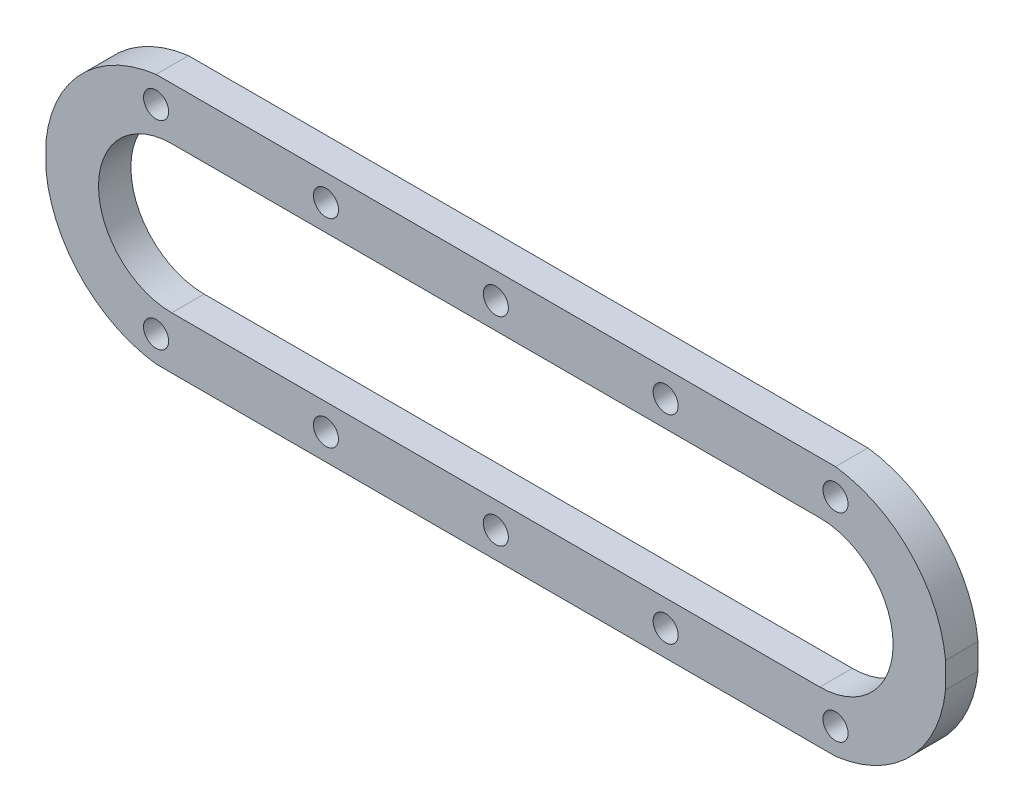
SolidWorks part; units mm, degrees
ref_plane "Front" through (0, 0, 0) normal (0, 0, 1) x (1, 0, 0)
ref_plane "Top" through (0, 0, 0) normal (0, 1, 0) x (1, 0, 0)
ref_plane "Right" through (0, 0, 0) normal (1, 0, 0) x (0, 0, -1)
sketch "Sketch1" plane through (0, 0, 0) normal (0, 0, 1) x (1, 0, 0)
  line L1 (88.138, 24.5745) -> (-88.138, 24.5745)
  line L2 (88.138, 24.5745) -> (88.138, -24.5745)
  line L3 (88.138, -24.5745) -> (-88.138, -24.5745)
  line L4 (-88.138, 24.5745) -> (-88.138, -24.5745)
  line L5 (88.138, 24.5745) -> (-88.138, -24.5745) construction
  line L6 (88.138, -24.5745) -> (-88.138, 24.5745) construction
  point P0 (0, 0)
  dimension "D1" = 176.276
  dimension "D2" = 49.149
extrude "Boss-Extrude1" add sketch "Sketch1" along normal blind 6.35
sketch "Sketch2" plane through (0, 0, 6.35) normal (0, 0, 1) x (1, 0, 0)
  line L0 (63.5, 0) -> (-63.5, 0) construction
  line L1 (63.5, -14.351) -> (-63.5, -14.351)
  line L2 (63.5, 14.351) -> (-63.5, 14.351)
  arc A0 (63.5, -14.351) -> (63.5, 14.351) centre (63.5, 0) ccw
  arc A1 (-63.5, 14.351) -> (-63.5, -14.351) centre (-63.5, 0) ccw
  point P2 (0, 0)
  dimension "D1" = 127
  dimension "D2" = 28.702
extrude "Cut-Extrude1" cut sketch "Sketch2" against normal through all
sketch "Sketch8" plane through (0, 0, 6.35) normal (0, 0, 1) x (1, 0, 0)
  line L4 (-63.5, 24.765) -> (63.5, 24.765)
  line L5 (-63.5, 14.351) -> (63.5, 14.351)
  line L6 (-63.5, -14.351) -> (63.5, -14.351)
  line L7 (-63.5, -24.765) -> (63.5, -24.765)
  arc A5 (-63.5, 14.351) -> (-63.5, -14.351) centre (-63.5, 0) ccw
  arc A6 (-63.5, 24.765) -> (-63.5, -24.765) centre (-63.5, 0) ccw
  arc A7 (63.5, 14.351) -> (63.5, -14.351) centre (63.5, 0) cw
  arc A8 (63.5, 24.765) -> (63.5, -24.765) centre (63.5, 0) cw
  line M5 (-88.138, 24.5745) -> (-88.138, -24.5745)
  line M6 (-88.138, -24.5745) -> (88.138, -24.5745)
  line M7 (88.138, -24.5745) -> (88.138, 24.5745)
  line M8 (88.138, 24.5745) -> (-88.138, 24.5745)
  dimension "D1" = 10.414
  dimension "D2" = 10.414
extrude "Cut-Extrude4" cut sketch "Sketch8" against normal through all contours A6 M8 M5 | A6 M5 M6 | A8 M8 M7 | A8 M7 M6
sketch "Sketch12" plane through (0, 0, 6.35) normal (0, 0, 1) x (1, 0, 0)
  circle A0 centre (-33.2829, 19.4627) radius 2.5527
  circle A1 centre (-66.5658, 19.4627) radius 2.5527
  circle A2 centre (0, 19.4627) radius 2.5527
  circle A3 centre (66.5658, 19.4627) radius 2.5527
  circle A4 centre (33.2829, 19.4628) radius 2.5527
  circle A5 centre (0, -19.4627) radius 2.5527
  circle A6 centre (-33.2829, -19.4627) radius 2.5527
  circle A7 centre (-66.5658, -19.4627) radius 2.5527
  circle A8 centre (33.2829, -19.4627) radius 2.5527
  circle A9 centre (66.5658, -19.4627) radius 2.5527
  dimension "D1" = 5.1054
hole_wizard "#10 (0.1935) Diameter Hole1" positions "Sketch15" profile "Sketch16" hole size "#10" standard "ANSI Inch" end condition through all
sketch "Sketch15" plane through (0, 0, 6.35) normal (0, 0, 1) x (1, 0, 0)
  point P0 (-66.5658, 19.4627)
  point P3 (-33.2829, 19.4627)
  point P6 (0, 19.4627)
  point P9 (33.2829, 19.4628)
  point P12 (66.5658, 19.4627)
  point P15 (66.5658, -19.4627)
  point P18 (33.2829, -19.4627)
  point P21 (0, -19.4627)
  point P24 (-33.2829, -19.4627)
  point P27 (-66.5658, -19.4627)
sketch "Sketch16" plane through (-66.5658, 19.4627, 6.35) normal (1, 0, 0) x (0, -1, 0)
  line L0 (0, 0) -> (0, 6.35)
  line L1 (0, 6.35) -> (2.4574, 6.35)
  line L2 (2.4574, 6.35) -> (2.4574, 0)
  line L5 (2.4574, 0) -> (0, 0)
  line L11 (0, -6.35) -> (0, 107.95) construction
  dimension "Thru Hole Dia." = 4.9149
  dimension "Thru Hole Depth" = 6.35
